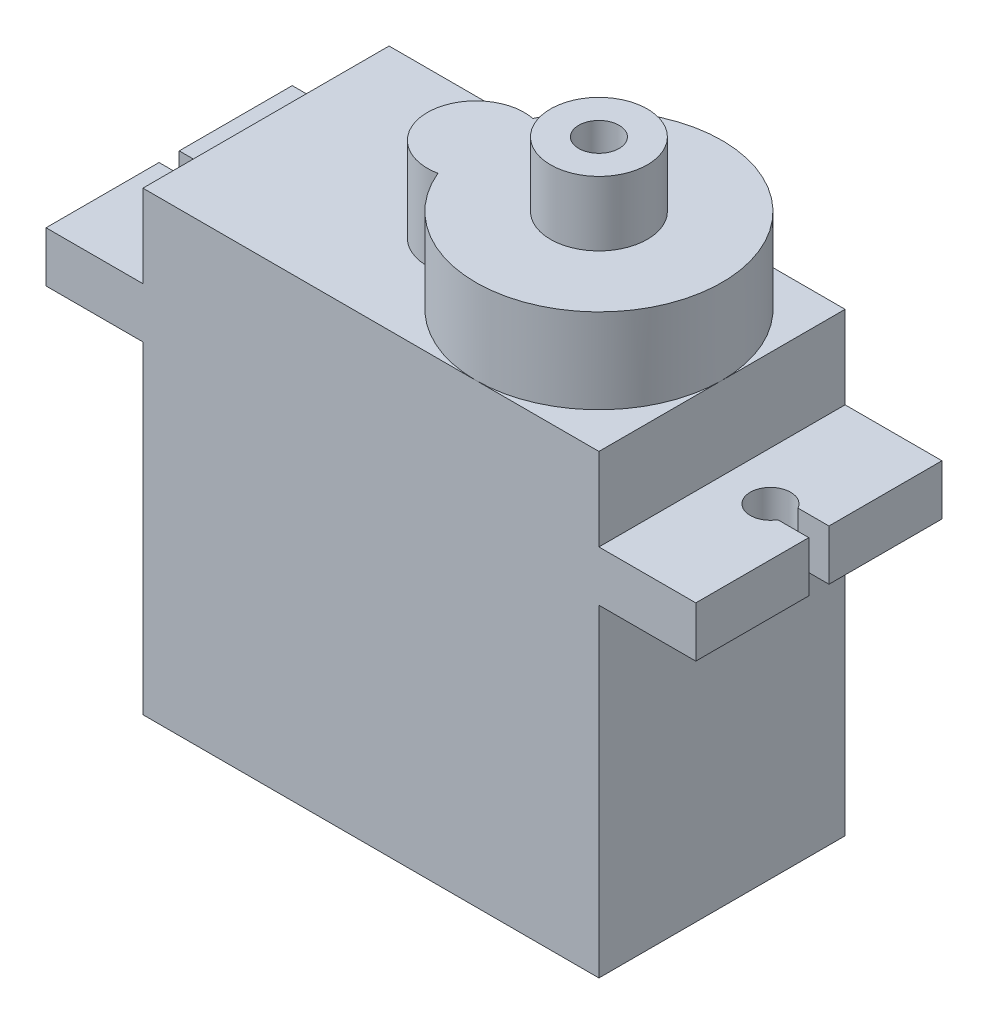
SolidWorks part; units mm, degrees
ref_plane "Front Plane" through (0, 0, 0) normal (0, 0, 1) x (1, 0, 0)
ref_plane "Top Plane" through (0, 0, 0) normal (0, 1, 0) x (1, 0, 0)
ref_plane "Right Plane" through (0, 0, 0) normal (1, 0, 0) x (0, 0, -1)
sketch "Sketch1" plane through (0, 0, 0) normal (0, 1, 0) x (1, 0, 0)
  line L1 (11.3, 6.1) -> (-11.3, 6.1)
  line L2 (11.3, 6.1) -> (11.3, -6.1)
  line L3 (11.3, -6.1) -> (-11.3, -6.1)
  line L4 (-11.3, 6.1) -> (-11.3, -6.1)
  line L5 (11.3, 6.1) -> (-11.3, -6.1) construction
  line L6 (11.3, -6.1) -> (-11.3, 6.1) construction
  point P0 (0, 0)
  dimension "D1" = 22.6
  dimension "D2" = 12.2
extrude "Boss-Extrude1" add sketch "Sketch1" along normal blind 22.6
sketch "Sketch4" plane through (-11.3, 0, 0) normal (-1, 0, 0) x (0, 0, 1)
  line L0 (6.1, 22.6) -> (6.1, 0) construction
  line L1 (-6.1, 22.6) -> (-6.1, 0) construction
  line L2 (-6.1, 16) -> (6.1, 16)
  line L3 (-6.1, 16) -> (-6.1, 18.5)
  line L4 (-6.1, 18.5) -> (6.1, 18.5)
  line L5 (6.1, 16) -> (6.1, 18.5)
  dimension "D1" = 2.5
  dimension "D2" = 16
extrude "Boss-Extrude2" add sketch "Sketch4" along normal blind 4.8
sketch "Sketch5" plane through (11.3, 0, 0) normal (1, 0, 0) x (0, 0, -1)
  line L0 (6.1, 22.6) -> (6.1, 0) construction
  line L1 (-6.1, 16) -> (6.1, 16)
  line L2 (-6.1, 16) -> (-6.1, 18.5)
  line L3 (-6.1, 18.5) -> (6.1, 18.5)
  line L4 (6.1, 16) -> (6.1, 18.5)
  dimension "D1" = 2.5
extrude "Boss-Extrude3" add sketch "Sketch5" along normal blind 4.8
sketch "Sketch8" plane through (0, 22.6, 0) normal (0, 1, 0) x (1, 0, 0)
  line L0 (11.3, -6.1) -> (11.3, 6.1) construction
  line L1 (11.3, 6.1) -> (-11.3, 6.1) construction
  arc A0 (-0.4279, -2.3531) -> (-0.4279, 2.3531) centre (5.2, 0) ccw
  arc A1 (-0.4279, 2.3531) -> (-0.4279, -2.3531) centre (-0.9, 0) ccw
  point P2 (11.3, 0)
  point P5 (-3.3, 0)
  point P9 (5.2, 6.1)
  point P10 (5.2, -6.1)
  dimension "D1" = 14.6
  dimension "D2" = 6.1
  dimension "D3" = 2.4
extrude "Boss-Extrude4" add sketch "Sketch8" along normal blind 4.2
sketch "Sketch9" plane through (0, 26.8, 0) normal (0, 1, 0) x (1, 0, 0)
  circle A0 centre (5.2, 0) radius 2.4
  arc A2 (-0.4279, 2.3531) -> (-0.4279, -2.3531) centre (-0.9, 0) ccw
  arc A3 (-0.4279, -2.3531) -> (-0.4279, 2.3531) centre (5.2, 0) ccw
  arc A4 (-0.4279, 2.3531) -> (-0.4279, -2.3531) centre (-0.9, 0) ccw construction
  arc A5 (-0.4279, -2.3531) -> (-0.4279, 2.3531) centre (5.2, 0) ccw construction
  dimension "D2" = 4.8
  dimension "D1" = 0
extrude "Boss-Extrude5" add sketch "Sketch9" along normal blind 3.2
sketch "Sketch10" plane through (0, 30, 0) normal (0, 1, 0) x (1, 0, 0)
  circle A0 centre (5.2, 0) radius 1
  circle A1 centre (5.2, 0) radius 2.4
  circle A2 centre (5.2, 0) radius 2.4 construction
  dimension "D2" = 2
  dimension "D1" = 0
extrude "Cut-Extrude1" cut sketch "Sketch10" against normal up to surface (3.2 mm away) up to face at (5.2, 26.8, 2.4)
sketch "Sketch12" plane through (0, 18.5, 0) normal (0, 1, 0) x (1, 0, 0)
  line L0 (13.7, 6.1) -> (13.7, -6.1) construction
  line L1 (16.1, 0) -> (11.3, 0) construction
  line L2 (16.1, 0.5) -> (16.1, -0.5)
  line L3 (16.1, 0.5) -> (14.566, 0.5)
  line L4 (11.3, 6.1) -> (11.3, -6.1)
  line L5 (11.3, -6.1) -> (16.1, -6.1)
  line L6 (16.1, -6.1) -> (16.1, 6.1)
  line L7 (16.1, 6.1) -> (11.3, 6.1)
  line L8 (11.3, 6.1) -> (11.3, -6.1)
  line L9 (11.3, -6.1) -> (16.1, -6.1)
  line L10 (16.1, -6.1) -> (16.1, 6.1) construction
  line L11 (16.1, 6.1) -> (11.3, 6.1) construction
  line L12 (16.1, -0.5) -> (14.566, -0.5)
  arc A0 (14.566, 0.5) -> (14.566, -0.5) centre (13.7, 0) ccw
  dimension "D2" = 2
  dimension "D3" = 1
  dimension "D1" = 0
extrude "Cut-Extrude2" cut sketch "Sketch12" against normal through all contours A0 L12 L2 L3
sketch "Sketch13" plane through (0, 18.5, 0) normal (0, 1, 0) x (1, 0, 0)
  line L0 (-13.7, 6.1) -> (-13.7, -6.1) construction
  line L1 (-16.1, 0) -> (-11.3, 0) construction
  line L2 (-16.1, 0.5) -> (-16.1, -0.5)
  line L3 (-16.1, 0.5) -> (-14.566, 0.5)
  line L4 (-11.3, -6.1) -> (-11.3, 6.1)
  line L5 (-11.3, 6.1) -> (-16.1, 6.1)
  line L6 (-16.1, 6.1) -> (-16.1, -6.1)
  line L7 (-16.1, -6.1) -> (-11.3, -6.1)
  line L8 (-11.3, -6.1) -> (-11.3, 6.1) construction
  line L9 (-11.3, 6.1) -> (-16.1, 6.1) construction
  line L10 (-16.1, 6.1) -> (-16.1, -6.1) construction
  line L11 (-16.1, -6.1) -> (-11.3, -6.1) construction
  line L12 (-16.1, -0.5) -> (-14.566, -0.5)
  arc A0 (-14.566, -0.5) -> (-14.566, 0.5) centre (-13.7, 0) ccw
  dimension "D2" = 2
  dimension "D3" = 1
  dimension "D1" = 0
extrude "Cut-Extrude3" cut sketch "Sketch13" against normal through all
